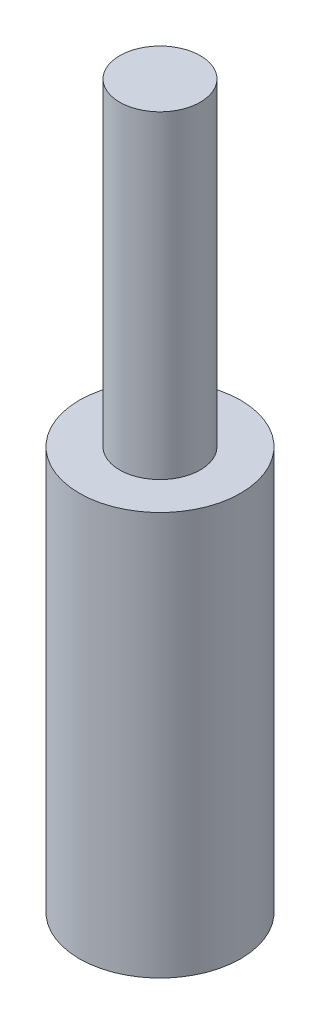
SolidWorks part; units mm, degrees
material "Polyethylene Cross-Linked"
ref_plane "Front Plane" through (0, 0, 0) normal (0, 0, 1) x (1, 0, 0)
ref_plane "Top Plane" through (0, 0, 0) normal (0, 1, 0) x (1, 0, 0)
ref_plane "Right Plane" through (0, 0, 0) normal (1, 0, 0) x (0, 0, -1)
sketch "Sketch1" plane through (0, 0, 0) normal (0, 1, 0) x (1, 0, 0)
  circle A0 centre (0, 0) radius 2
  dimension "D1" = 4
extrude "Boss-Extrude1" add sketch "Sketch1" along normal blind 10
sketch "Sketch2" plane through (0, 10, 0) normal (0, 1, 0) x (1, 0, 0)
  circle A0 centre (0, 0) radius 1
  dimension "D1" = 2
extrude "Boss-Extrude2" add sketch "Sketch2" along normal blind 7.9
ref_plane "Plane1" through (0, 0, 2) normal (0, 0, 1) x (1, 0, 0)
sketch "Sketch3" plane through (0, 0, 2) normal (0, 0, 1) x (1, 0, 0)
  line L0 (0, 0) -> (0, 10) construction
  line L1 (2, 10) -> (-2, 10) construction
  line L2 (0, 7.4) -> (0, 3) construction
  line L3 (1.5, 7.4) -> (1.5, 3)
  line L4 (-1.5, 7.4) -> (-1.5, 3)
  arc A0 (1.5, 7.4) -> (-1.5, 7.4) centre (0, 7.4) ccw
  arc A1 (-1.5, 3) -> (1.5, 3) centre (0, 3) ccw
  point P3 (0, 5.2)
  dimension "D1" = 1.5
  dimension "D2" = 3
  dimension "D3" = 4.4
extrude "Cut-Extrude1" [suppressed] cut sketch "Sketch3" against normal blind 10
